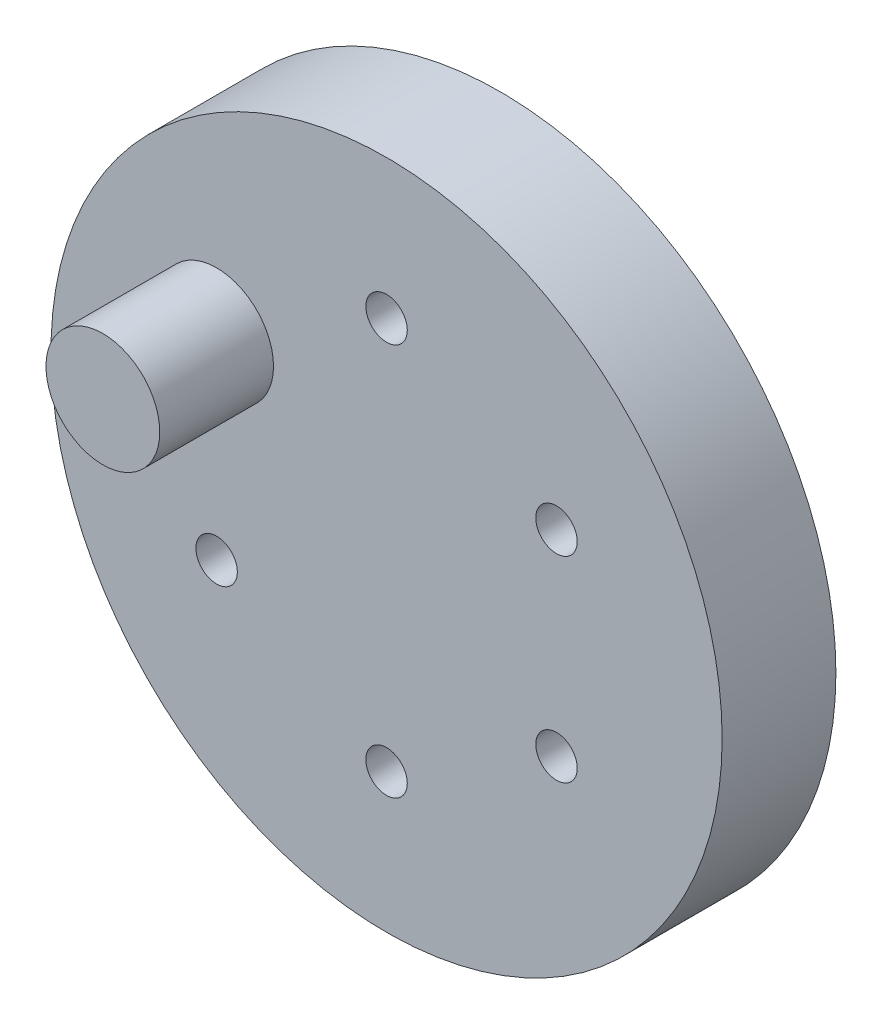
SolidWorks part; units mm, degrees
ref_plane "前视基准面" through (0, 0, 0) normal (0, 0, 1) x (1, 0, 0)
ref_plane "上视基准面" through (0, 0, 0) normal (0, 1, 0) x (1, 0, 0)
ref_plane "右视基准面" through (0, 0, 0) normal (1, 0, 0) x (0, 0, -1)
sketch "草图1" plane through (0, 0, 0) normal (0, 0, 1) x (1, 0, 0)
  circle A0 centre (0, 0) radius 29.5
  circle A1 centre (0, 17.25) radius 1.8214
  circle A2 centre (14.9389, 8.625) radius 1.8214
  circle A3 centre (14.9389, -8.625) radius 1.8214
  circle A4 centre (0, -17.25) radius 1.8214
  circle A5 centre (-14.9389, -8.625) radius 1.8214
  circle A6 centre (-14.9389, 8.625) radius 1.8214
  point P7 (0, 0)
  point P18 (0, 0)
  point P19 (0, 15.4286)
  dimension "D1" = 17.25
  dimension "D2" = 59
  dimension "D4" = 3.6427
  dimension "D3" = 6
extrude "凸台-拉伸1" add sketch "草图1" along normal blind 10
sketch "草图2" plane through (0, 0, 10) normal (0, 0, 1) x (1, 0, 0)
  circle A0 centre (-14.9389, 8.625) radius 5
extrude "凸台-拉伸2" add sketch "草图2" along normal blind 10
